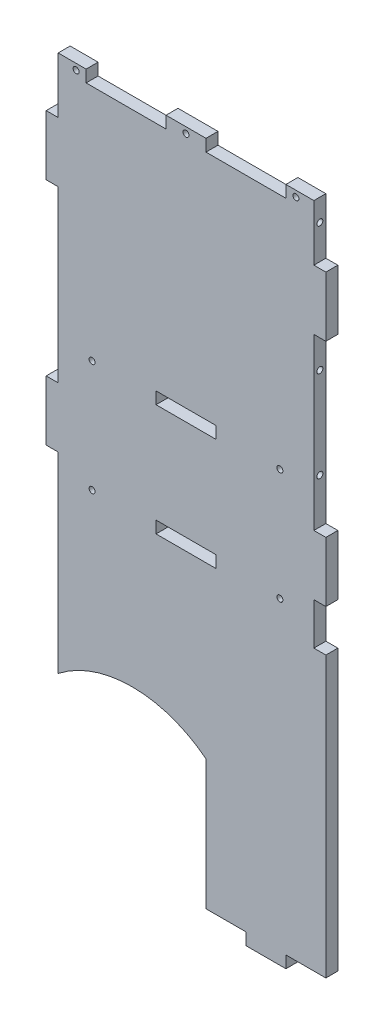
SolidWorks part; units mm, degrees
ref_plane "Plan de face" through (0, 0, 0) normal (0, 0, 1) x (1, 0, 0)
ref_plane "Plan de dessus" through (0, 0, 0) normal (0, 1, 0) x (1, 0, 0)
ref_plane "Plan de droite" through (0, 0, 0) normal (1, 0, 0) x (0, 0, -1)
sketch "Esquisse1" plane through (0, 0, 0) normal (0, 0, 1) x (1, 0, 0)
  line L0 (16.4964, 68.7878) -> (16.4964, 65.7878) construction
  line L1 (-0.0036, 68.7878) -> (139.9964, 68.7878)
  line L2 (-0.0036, 68.7878) -> (-0.0036, -271.2122)
  line L3 (-0.0036, -271.2122) -> (139.9964, -271.2122)
  line L4 (139.9964, 68.7878) -> (139.9964, -271.2122)
  line L5 (54.9964, -109.2122) -> (84.9964, -109.2122)
  line L6 (54.9964, -109.2122) -> (54.9964, -115.2122)
  line L7 (54.9964, -115.2122) -> (84.9964, -115.2122)
  line L8 (84.9964, -109.2122) -> (84.9964, -115.2122)
  line L9 (19.9964, 68.7878) -> (119.9964, 68.7878)
  line L11 (19.9964, 68.7878) -> (119.9964, 68.7878)
  line L13 (69.9964, 68.7878) -> (69.9964, -271.2122) construction
  circle A0 centre (14.9964, 65.7878) radius 1.5
  circle A1 centre (124.9964, 65.7878) radius 1.5
  circle A2 centre (69.9964, 65.7878) radius 1.5
  circle A6 centre (22.9964, -112.2122) radius 1.5
  circle A7 centre (116.9964, -112.2122) radius 1.5
  dimension "D3" = 3
  dimension "D6" = 3
  dimension "D9" = 3
  dimension "D24" = 3
  dimension "D25" = 3
  dimension "D27" = 3
  dimension "D28" = 3
  dimension "D8" = 3
  dimension "D1" = 140
  dimension "D2" = 340
  dimension "D4" = 15
  dimension "D5" = 15
  dimension "D7" = 3
  dimension "D12" = 23
  dimension "D13" = 23
  dimension "D14" = 156
  dimension "D15" = 6
  dimension "D16" = 55
  dimension "D17" = 30
  dimension "D29" = 3
sketch "Esquisse4" plane through (0, 0, 0) normal (0, 0, 1) x (1, 0, 0)
  line L0 (-0.0036, 68.7878) -> (-0.0036, -271.2122) construction
  line L1 (-0.0036, 68.7878) -> (5.9964, 68.7878)
  line L2 (-0.0036, 68.7878) -> (-0.0036, 40.7878)
  line L3 (-0.0036, 40.7878) -> (5.9964, 40.7878)
  line L4 (5.9964, 68.7878) -> (5.9964, 40.7878)
  line L5 (-0.0036, 10.7878) -> (5.9964, 10.7878)
  line L6 (-0.0036, 10.7878) -> (-0.0036, -74.2122)
  line L7 (-0.0036, -74.2122) -> (5.9964, -74.2122)
  line L8 (5.9964, 10.7878) -> (5.9964, -74.2122)
  line L9 (69.9964, 65.7878) -> (69.9964, -271.2122) construction
  line L10 (-0.0036, -104.2122) -> (5.9964, -104.2122)
  line L11 (-0.0036, -104.2122) -> (-0.0036, -155.2122)
  line L12 (-0.0036, -155.2122) -> (5.9964, -155.2122)
  line L13 (5.9964, -104.2122) -> (5.9964, -155.2122)
  line L14 (-0.0036, -271.2122) -> (139.9964, -271.2122) construction
  line L15 (139.9964, -104.2122) -> (133.9964, -104.2122)
  line L16 (133.9964, -104.2122) -> (133.9964, -125.2122)
  line L17 (133.9964, -125.2122) -> (139.9964, -125.2122)
  line L18 (139.9964, -125.2122) -> (139.9964, -104.2122)
  line L19 (139.9964, -74.2122) -> (133.9964, -74.2122)
  line L20 (139.9964, 10.7878) -> (139.9964, -74.2122)
  line L21 (133.9964, 10.7878) -> (133.9964, -74.2122)
  line L22 (139.9964, 10.7878) -> (133.9964, 10.7878)
  line L23 (139.9964, 68.7878) -> (133.9964, 68.7878)
  line L24 (139.9964, 40.7878) -> (133.9964, 40.7878)
  line L25 (139.9964, 68.7878) -> (139.9964, 40.7878)
  line L26 (133.9964, 68.7878) -> (133.9964, 40.7878)
  line L27 (139.9964, 68.7878) -> (139.9964, -222.3339) construction
  line L28 (190.2583, -271.2122) -> (43.4436, -271.2122) construction
  dimension "D1" = 6
  dimension "D2" = 28
  dimension "D3" = 30
  dimension "D4" = 85
  dimension "D5" = 30
  dimension "D6" = 51
  dimension "D7" = 30
  dimension "D8" = 21
  dimension "D9" = 6
extrude "Boss.-Extru.3" add sketch "Esquisse1" along normal blind 6
extrude "Enlèv. mat.-Extru.2" cut sketch "Esquisse4" along normal blind 6
sketch "Esquisse5" plane through (0, 0, 0) normal (1, 0, 0) x (0, 0, -1)
  line L0 (0, -125.6726) -> (0, 121.1593) construction
  line L1 (0, 121.1593) -> (0, 30.1192) construction
  line L2 (-6, -104.2122) -> (0, -104.2122) construction
  line L3 (-6, -74.2122) -> (0, -74.2122) construction
  line L4 (-6, 10.7878) -> (0, 10.7878) construction
  line L5 (-6, 40.7878) -> (0, 40.7878) construction
  circle A0 centre (-3, -126.7122) radius 1.5
  circle A1 centre (-3, -51.7122) radius 1.5
  circle A2 centre (-3, -6.2122) radius 1.5
  circle A3 centre (-3, 57.7878) radius 1.5
  point P5 (-3, -104.2122)
  point P11 (-3, -74.2122)
  point P20 (-3, 40.7878)
  dimension "D1" = 3
  dimension "D2" = 22.5
  dimension "D3" = 22.5
  dimension "D4" = 17
  dimension "D5" = 17
sketch "Esquisse6" plane through (133.9964, 0, 0) normal (1, 0, 0) x (0, 0, -1)
  line L0 (-6, 10.7878) -> (0, 10.7878) construction
  line L1 (-6, 10.7878) -> (-6, -74.2122) construction
  line L2 (-6, -74.2122) -> (0, -74.2122) construction
  line L3 (-3, -6.2122) -> (-3, -51.7122) construction
  line L5 (-6, 40.7878) -> (0, 40.7878) construction
  circle A0 centre (-3, -6.2122) radius 1.5
  circle A1 centre (-3, -51.7122) radius 1.5
  circle A3 centre (-3, 57.7878) radius 1.5
  point P8 (-3, -74.2122)
  point P17 (-3, 40.7878)
  dimension "D1" = 17
  dimension "D3" = 22.5
  dimension "D5" = 17
  dimension "D2" = 3
extrude "Enlèv. mat.-Extru.3" cut sketch "Esquisse5" along normal blind 9
extrude "Enlèv. mat.-Extru.6" cut sketch "Esquisse6" against normal blind 3
sketch "Esquisse7" plane through (0, 0, 0) normal (0, 0, 1) x (1, 0, 0)
  line L0 (-0.0036, -271.2122) -> (139.9964, -271.2122) construction
  line L1 (139.9964, -271.2122) -> (119.9964, -271.2122)
  line L2 (139.9964, -271.2122) -> (139.9964, -265.2122)
  line L3 (139.9964, -265.2122) -> (119.9964, -265.2122)
  line L4 (119.9964, -271.2122) -> (119.9964, -265.2122)
  line L5 (99.9964, -265.2122) -> (79.9964, -265.2122)
  line L6 (99.9964, -265.2122) -> (99.9964, -271.2122)
  line L7 (99.9964, -271.2122) -> (79.9964, -271.2122)
  line L8 (79.9964, -265.2122) -> (79.9964, -271.2122)
  dimension "D1" = 20
  dimension "D2" = 6
  dimension "D3" = 20
  dimension "D4" = 20
  dimension "D5" = 6
extrude "Enlèv. mat.-Extru.7" cut sketch "Esquisse7" along normal blind 10
sketch "Esquisse8" plane through (0, 0, 6) normal (0, 0, 1) x (1, 0, 0)
  line L0 (79.9964, -271.2122) -> (79.9964, -265.2122) construction
  line L1 (99.9964, -265.2122) -> (79.9964, -265.2122) construction
  line L2 (79.9964, -265.2122) -> (79.9964, -200.2122)
  line L3 (5.9964, -200.2122) -> (5.9964, -155.2122)
  line L4 (-0.0036, -271.2122) -> (79.9964, -271.2122) construction
  line L5 (5.9964, -271.2122) -> (5.9964, -155.2122) construction
  line L6 (5.9964, -155.2122) -> (-0.0036, -155.2122)
  line L8 (-0.0036, -155.2122) -> (-0.0036, -271.2122)
  line L9 (-0.0036, -271.2122) -> (79.9964, -271.2122)
  line L10 (79.9964, -271.2122) -> (79.9964, -265.2122)
  arc A1 (5.9964, -200.2122) -> (79.9964, -200.2122) centre (42.9964, -247.4457) cw
  dimension "D2" = 65
  dimension "D3" = 71
  dimension "D1" = 74
  dimension "D4" = 60
extrude "Enlèv. mat.-Extru.8" cut sketch "Esquisse8" against normal blind 6
sketch "Esquisse9" plane through (0, 0, 6) normal (0, 0, 1) x (1, 0, 0)
  line L0 (19.9964, 68.7878) -> (19.9964, 62.7878)
  line L1 (5.9964, 68.7878) -> (133.9964, 68.7878) construction
  line L2 (19.9964, 62.7878) -> (59.9964, 62.7878)
  line L3 (59.9964, 62.7878) -> (59.9964, 68.7878)
  line L4 (19.9964, 68.7878) -> (59.9964, 68.7878)
  line L5 (79.9964, 68.7878) -> (79.9964, 62.7878)
  line L6 (79.9964, 62.7878) -> (119.9964, 62.7878)
  line L7 (119.9964, 62.7878) -> (119.9964, 68.7878)
  line L8 (119.9964, 68.7878) -> (79.9964, 68.7878)
  line L9 (5.9964, 40.7878) -> (5.9964, 68.7878) construction
  line L10 (133.9964, 68.7878) -> (133.9964, 40.7878) construction
  dimension "D1" = 6
  dimension "D2" = 6
  dimension "D3" = 14
  dimension "D4" = 14
  dimension "D5" = 40
  dimension "D6" = 40
extrude "Enlèv. mat.-Extru.9" cut sketch "Esquisse9" against normal blind 6
sketch "Esquisse10" plane through (0, 0, 0) normal (0, 0, -1) x (-1, 0, 0)
  line L0 (-84.9964, -53.2122) -> (-84.9964, -59.2122)
  line L1 (-84.9964, -59.2122) -> (-54.9964, -59.2122)
  line L2 (-54.9964, -59.2122) -> (-54.9964, -53.2122)
  line L3 (-54.9964, -53.2122) -> (-84.9964, -53.2122)
  line L4 (-54.9964, -109.2122) -> (-84.9964, -109.2122) construction
  line L6 (-5.9964, -74.2122) -> (-5.9964, 10.7878) construction
  line L7 (-133.9964, 10.7878) -> (-133.9964, -74.2122) construction
  circle A0 centre (-116.9964, -56.2122) radius 1.5
  circle A1 centre (-22.9964, -56.2122) radius 1.5
  circle A3 centre (-22.9964, -112.2122) radius 1.5 construction
  dimension "D7" = 3
  dimension "D8" = 3
  dimension "D9" = 3
  dimension "D10" = 56
  dimension "D1" = 50
  dimension "D2" = 6
  dimension "D3" = 49
  dimension "D4" = 49
  dimension "D5" = 32
  dimension "D6" = 32
extrude "Enlèv. mat.-Extru.10" cut sketch "Esquisse10" against normal blind 6
